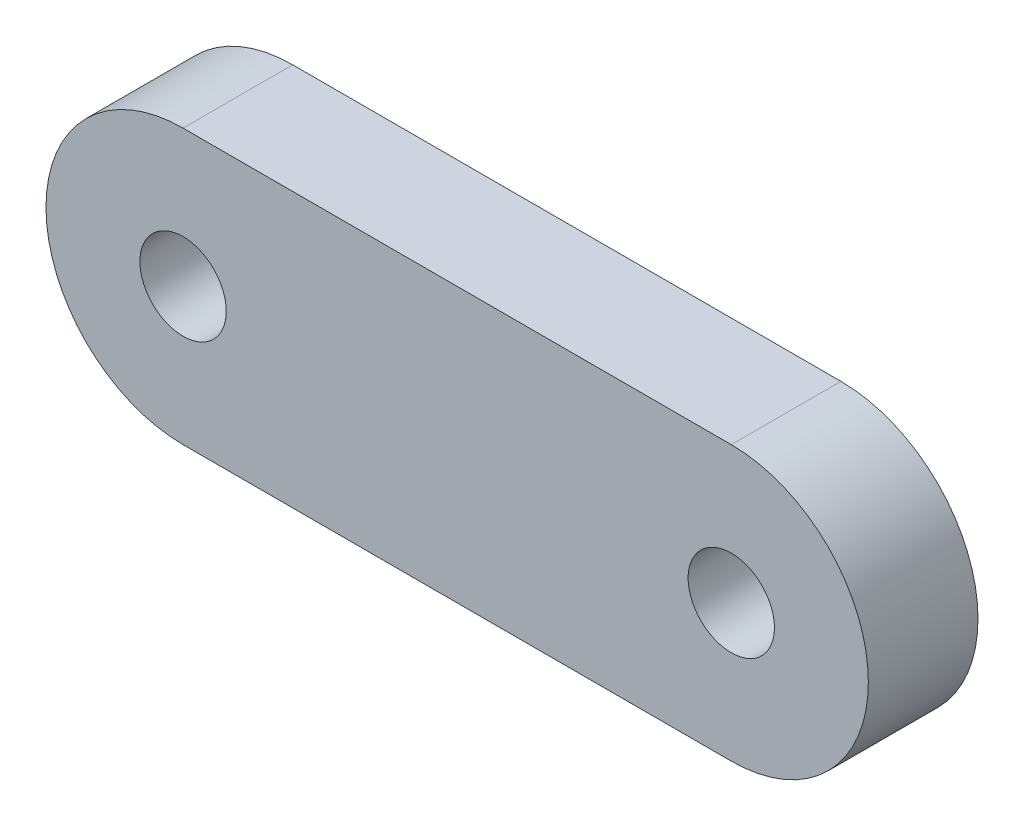
SolidWorks part; units mm, degrees
ref_plane "Front Plane" through (0, 0, 0) normal (0, 0, 1) x (1, 0, 0)
ref_plane "Top Plane" through (0, 0, 0) normal (0, 1, 0) x (1, 0, 0)
ref_plane "Right Plane" through (0, 0, 0) normal (1, 0, 0) x (0, 0, -1)
sketch "Sketch1" plane through (0, 0, 0) normal (0, 0, 1) x (1, 0, 0)
  line L0 (0, 0) -> (25.4, 0) construction
  line L1 (0, 6.35) -> (25.4, 6.35)
  line L2 (0, -6.35) -> (25.4, -6.35)
  arc A0 (0, 6.35) -> (0, -6.35) centre (0, 0) ccw
  arc A1 (25.4, -6.35) -> (25.4, 6.35) centre (25.4, 0) ccw
  circle A2 centre (0, 0) radius 2
  circle A3 centre (25.4, 0) radius 2
  point P3 (12.7, 0)
  dimension "D2" = 6.35
  dimension "D3" = 4
  dimension "D1" = 25.4
extrude "Boss-Extrude1" add sketch "Sketch1" along normal blind 5.08
